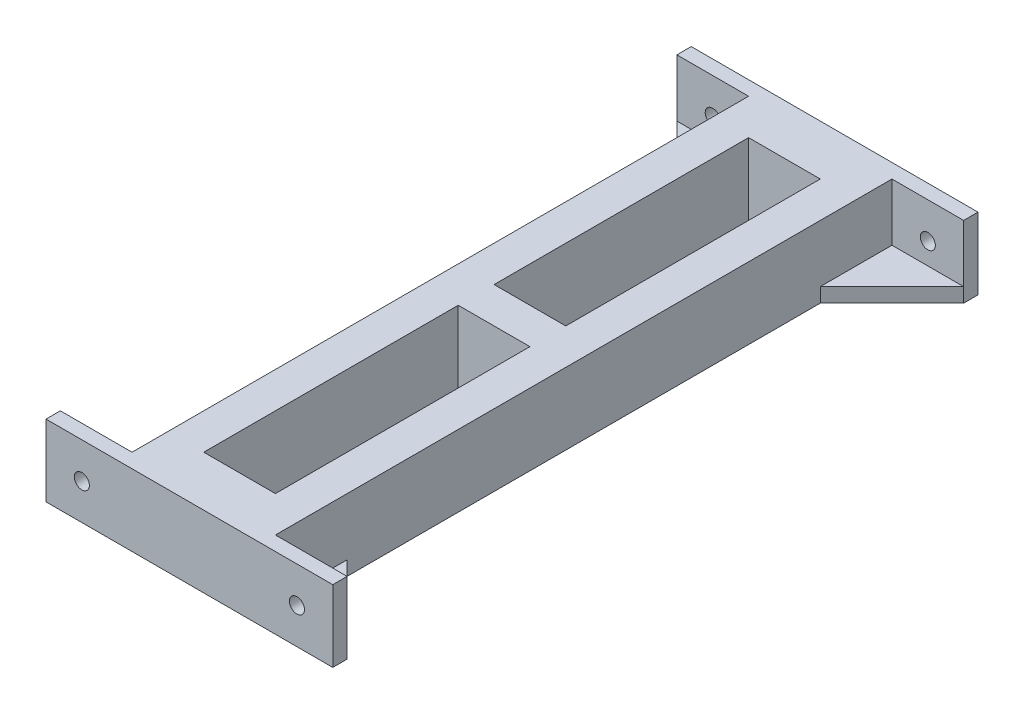
SolidWorks part; units mm, degrees
ref_plane "Front Plane" through (0, 0, 0) normal (0, 0, 1) x (1, 0, 0)
ref_plane "Top Plane" through (0, 0, 0) normal (0, 1, 0) x (1, 0, 0)
ref_plane "Right Plane" through (0, 0, 0) normal (1, 0, 0) x (0, 0, -1)
sketch "Sketch1" plane through (0, 0, 0) normal (0, 1, 0) x (1, 0, 0)
  line L0 (0, 0) -> (0, 4)
  line L1 (0, 180) -> (80, 180)
  line L2 (80, 180) -> (80, 176)
  line L3 (80, 0) -> (0, 0)
  line L4 (0, 180) -> (20, 180)
  line L5 (20, 176) -> (20, 4)
  line L6 (80, 180) -> (60, 180)
  line L7 (60, 176) -> (60, 4)
  line L8 (0, 180) -> (0, 176)
  line L9 (0, 176) -> (20, 176)
  line L10 (60, 176) -> (80, 176)
  line L11 (80, 0) -> (80, 4)
  line L12 (80, 4) -> (60, 4)
  line L13 (0, 176) -> (0, 180)
  line L14 (80, 4) -> (80, 0)
  line L15 (20, 4) -> (0, 4)
extrude "Boss-Extrude1" add sketch "Sketch1" along normal blind 20 contours L5 L15 L0 L3 L11 L12 L7 L10 L2 L1 L8 L9
sketch "Sketch2" plane through (0, 0, 0) normal (0, -1, 0) x (1, 0, 0)
  line L0 (80, -176) -> (60, -176)
  line L1 (60, -176) -> (60, -156)
  line L2 (60, -176) -> (60, -4) construction
  line L3 (60, -156) -> (80, -176)
  line L4 (20, -176) -> (0, -176)
  line L5 (0, -176) -> (20, -176)
  line L6 (20, -176) -> (20, -156)
  line L7 (20, -176) -> (20, -4) construction
  line L8 (20, -156) -> (0, -176)
  line L9 (80, -4) -> (60, -4)
  line L10 (60, -4) -> (60, -24)
  line L11 (60, -24) -> (80, -4)
  line L12 (0, -4) -> (20, -4)
  line L13 (0, 0) -> (0, -4) construction
  line L14 (20, -4) -> (0, -4) construction
  line L15 (20, -4) -> (20, -24)
  line L16 (20, -24) -> (0, -4)
  line M1 (20, -4) -> (20, -176)
  line M2 (20, -176) -> (0, -176)
  line M6 (80, -176) -> (60, -176)
  line M7 (60, -176) -> (60, -4)
  line M8 (60, -4) -> (80, -4)
  line M12 (0, -4) -> (20, -4)
extrude "Boss-Extrude2" add sketch "Sketch2" against normal blind 4 contours L11 M7 M8 | L16 M1 M12 | L8 M1 M2 | L3 M7 M6
sketch "Sketch3" plane through (0, 20, 0) normal (0, 1, 0) x (1, 0, 0)
  line L0 (50, 14) -> (50, 85)
  line L1 (60, 4) -> (20, 4)
  line L2 (60, 4) -> (60, 176)
  line L3 (60, 176) -> (20, 176)
  line L4 (20, 4) -> (20, 176)
  line L5 (50, 166) -> (30, 166)
  line L6 (30, 14) -> (30, 85)
  line L7 (50, 14) -> (30, 14)
  line L9 (50, 95) -> (30, 95)
  line L10 (50, 85) -> (30, 85)
  line L11 (50, 95) -> (50, 166)
  line L12 (50, 14) -> (50, 166) construction
  line L14 (30, 95) -> (30, 166)
  line L15 (30, 14) -> (30, 166) construction
  dimension "D1" = 10
extrude "Cut-Extrude1" cut sketch "Sketch3" against normal blind 55 contours L0 L10 L6 L7 | L5 L14 L9 L11
sketch "Sketch6" plane through (0, 0, 0) normal (0, 0, 1) x (1, 0, 0)
  line L0 (0, 10) -> (10, 10)
  line L1 (0, 20) -> (0, 0) construction
  line L2 (80, 10) -> (70, 10)
  line L3 (80, 20) -> (80, 0) construction
  circle A0 centre (10, 10) radius 2.1
  circle A1 centre (70, 10) radius 2.1
extrude "Cut-Extrude2" cut sketch "Sketch6" against normal blind 207
